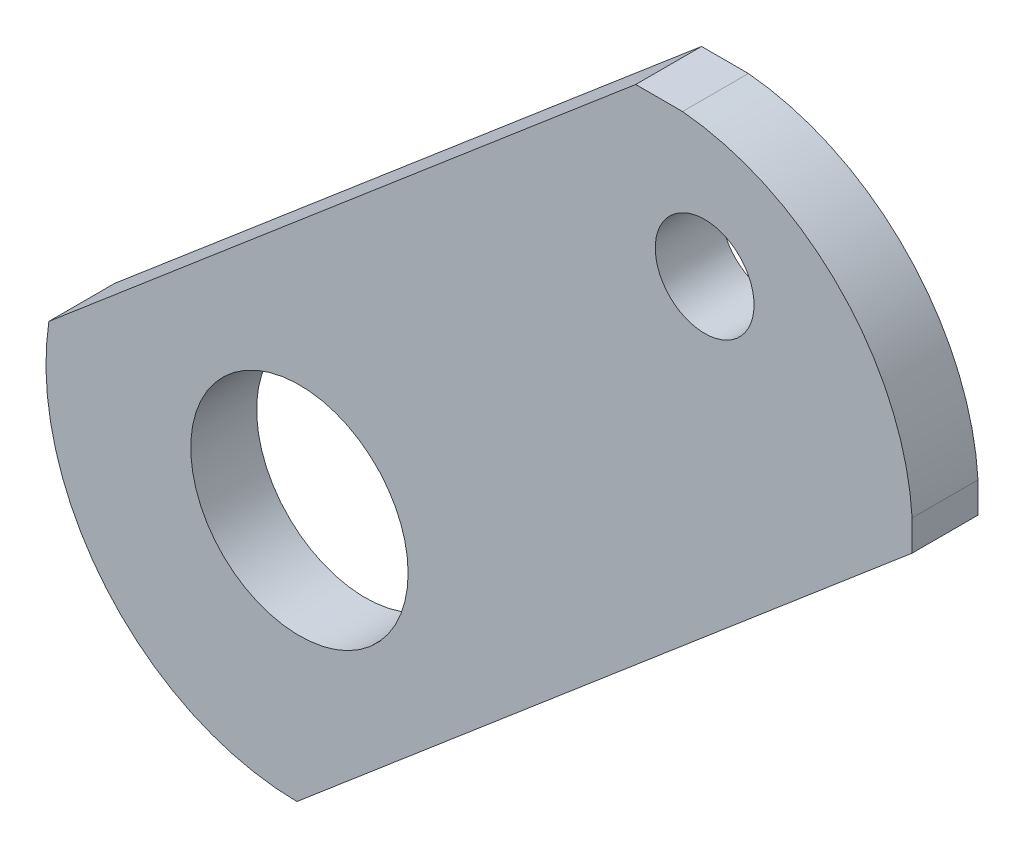
SolidWorks part; units mm, degrees
ref_plane "Front Plane" through (0, 0, 0) normal (0, 0, 1) x (1, 0, 0)
ref_plane "Top Plane" through (0, 0, 0) normal (0, 1, 0) x (1, 0, 0)
ref_plane "Right Plane" through (0, 0, 0) normal (1, 0, 0) x (0, 0, -1)
sketch "Sketch1" plane through (0, 0, 0) normal (0, 0, 1) x (1, 0, 0)
  line L0 (-38.1, 0) -> (-38.1, -30.48)
  line L3 (0, 0) -> (-38.1, 0)
  line L6 (-38.1, -30.48) -> (0, -30.48)
  line L7 (0, -30.48) -> (0, 0)
  point P0 (-19.05, 0)
  dimension "D1" = 30.48
  dimension "D2" = 38.1
extrude "Boss-Extrude1" add sketch "Sketch1" along normal blind 2.54 contours L3 L0 L6 L7
sketch "Sketch2" plane through (0, 0, 2.54) normal (0, 0, 1) x (1, 0, 0)
  line L0 (0, -30.48) -> (0, 0) construction
  line L1 (0, 0) -> (-38.1, 0) construction
  line L2 (0, -5.08) -> (-38.1, -5.08) construction
  line L3 (-8.001, -5.08) -> (-30.099, -5.08) construction
  line L7 (-38.1, 0) -> (-38.1, -30.48) construction
  line L8 (-8.001, -5.08) -> (-23.6266, -20.7056) construction
  circle A1 centre (-8.001, -5.08) radius 1.905
  circle A2 centre (-23.6266, -20.7056) radius 4.191
  point P4 (-19.05, -5.08)
  point P5 (-19.05, -5.08)
  point P8 (-19.05, 0)
  point P14 (-19.05, -5.08)
  dimension "D1" = 3.81
  dimension "D3" = 5.08
  dimension "D4" = 45
  dimension "D6" = 8.382
  dimension "D5" = 22.098
  dimension "D7" = 22.098
extrude "Cut-Extrude1" cut sketch "Sketch2" against normal through all
sketch "Sketch3" plane through (0, 0, 2.54) normal (0, 0, 1) x (1, 0, 0)
  line L0 (0, -10.3225) -> (-23.7262, -30.48)
  line L1 (0, -30.48) -> (0, 0) construction
  line L2 (-38.1, -30.48) -> (0, -30.48) construction
  line L3 (-23.7262, -30.48) -> (0, -30.48)
  line L4 (0, -30.48) -> (0, -10.3225)
  line L5 (-38.1, 0) -> (-10.6606, 0)
  line L6 (0, 0) -> (-38.1, 0) construction
  line L7 (-10.6606, 0) -> (-38.1, -23.3122)
  line L8 (-38.1, 0) -> (-38.1, -30.48) construction
  line L9 (-38.1, -23.3122) -> (-38.1, 0)
  line L10 (-12.5468, -20.9822) -> (-22.1093, -9.7267) construction
  line L11 (-23.6266, -20.7056) -> (-17.3281, -15.3544) construction
  point P18 (-23.6266, -20.7056)
  point P19 (-17.3281, -15.3544)
  dimension "D1" = 14.7691
extrude "Cut-Extrude3" cut sketch "Sketch3" against normal blind 2.54
sketch "Sketch4" plane through (0, 0, 2.54) normal (0, 0, 1) x (1, 0, 0)
  line L0 (-23.6266, -30.4805) -> (-38.1, -30.48)
  line L1 (-38.1, -30.48) -> (-38.1, -23.3122)
  line L2 (-38.1, -23.3122) -> (-33.2887, -19.2246)
  line L3 (-38.1, -23.3122) -> (-10.6606, 0) construction
  arc A0 (-33.2887, -19.2246) -> (-23.627, -30.4805) centre (-23.6266, -20.7056) ccw
  line M1 (-10.6606, 0) -> (-38.1, -23.3122)
  line M2 (-38.1, -23.3122) -> (-38.1, -30.48)
  line M3 (-38.1, -30.48) -> (-23.7262, -30.48)
extrude "Cut-Extrude4" cut sketch "Sketch4" against normal blind 2.54 contours A0 M1 M2 M3
sketch "Sketch5" plane through (0, 0, 2.54) normal (0, 0, 1) x (1, 0, 0)
  line L0 (-10.6606, 0) -> (0, 0)
  line L1 (0, 0) -> (0, -10.3225)
  arc A0 (-10.6606, 0) -> (0, -10.3225) centre (-9.7571, -9.733) cw
  arc A1 (-33.2887, -19.2246) -> (-23.7262, -30.48) centre (-23.6266, -20.7056) ccw construction
  line M7 (0, 0) -> (-10.6606, 0)
extrude "Cut-Extrude5" cut sketch "Sketch5" against normal blind 2.54 contours A0 L1 M7
